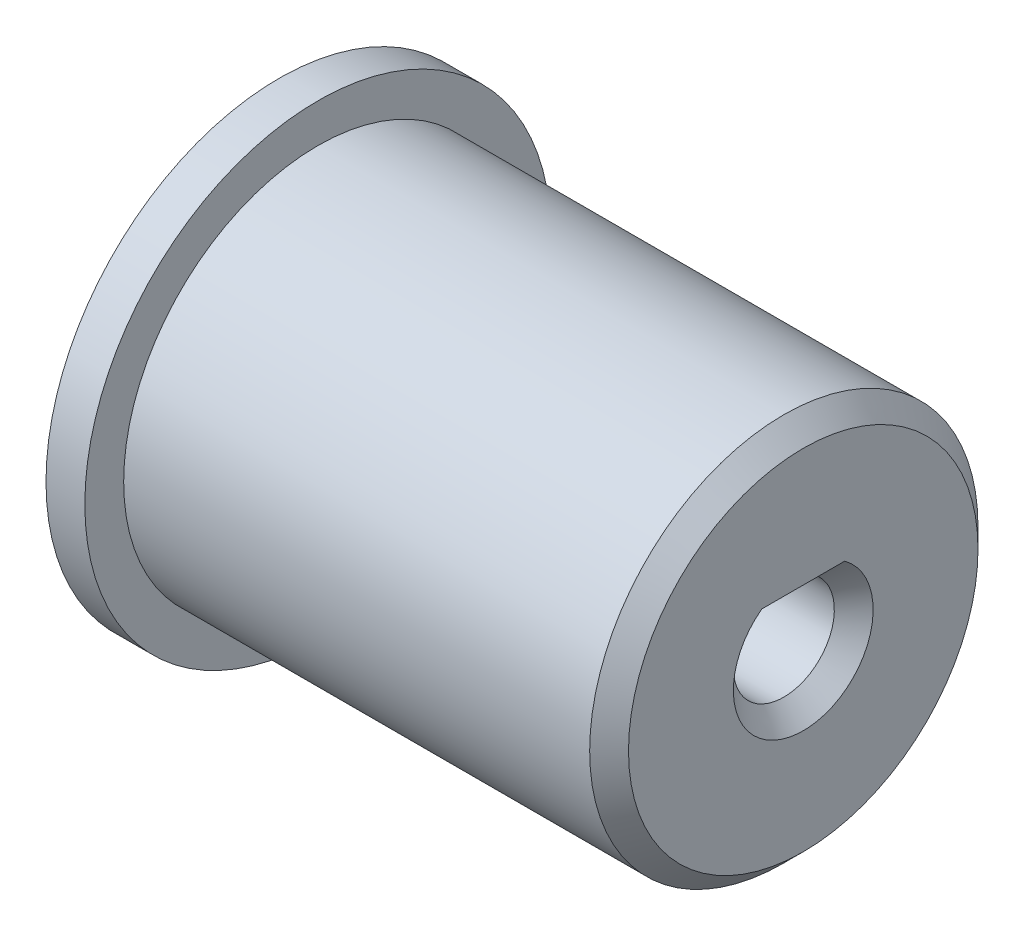
SolidWorks part; units mm, degrees
ref_plane "Ebene vorne" through (0, 0, 0) normal (0, 0, 1) x (1, 0, 0)
ref_plane "Ebene oben" through (0, 0, 0) normal (0, 1, 0) x (1, 0, 0)
ref_plane "Ebene rechts" through (0, 0, 0) normal (1, 0, 0) x (0, 0, -1)
sketch "Skizze2" plane through (0, 0, 0) normal (1, 0, 0) x (0, 0, -1)
  circle A0 centre (0, 0) radius 10
  dimension "D1" = 20
extrude "Aufsatz-Linear austragen1" add sketch "Skizze2" along normal blind 25
sketch "Skizze3" plane through (0, 0, 0) normal (-1, 0, 0) x (0, 0, 1)
  circle A0 centre (0, 0) radius 12
  dimension "D1" = 24
extrude "Aufsatz-Linear austragen2" add sketch "Skizze3" along normal blind 2
sketch "Skizze4" plane through (25, 0, 0) normal (1, 0, 0) x (0, 0, -1)
  line L0 (-1.7748, 1.9) -> (1.7748, 1.9)
  line L1 (-6.4521, 0) -> (8.6873, 0) construction
  arc A0 (-1.7748, 1.9) -> (1.7748, 1.9) centre (0, 0) ccw
  point P5 (0, -2.6)
  dimension "D1" = 2.6
  dimension "D2" = 4.5
extrude "Schnitt-Linear austragen1" cut sketch "Skizze4" against normal blind 15
chamfer "Fase1" distance 1 angle 45 2 edges at (25, 1.9, 0) (25, -2.6, 0)
chamfer "Fase2" distance 1 angle 45 1 edges at (25, 0, -10)
hole_wizard "Ø3.1 (3.1) Durchmesser Bohrung1" positions "Skizze5" profile "Skizze6" hole size "Ø3.1" standard "ISO"
sketch "Skizze5" plane through (-2, 0, 0) normal (-1, 0, 0) x (0, 0, 1)
  line L0 (0, 0) -> (-50000, 0) construction
  line L1 (0, 0) -> (0, -50000) construction
  point P5 (-4.25, 0)
  point P7 (4.25, 0)
  dimension "D1" = 8.5
sketch "Skizze6" plane through (-2, 0, 4.25) normal (0, 1, 0) x (0, 0, 1)
  line L0 (0, 0) -> (0, 7.9313)
  line L1 (0, 7.9313) -> (1.55, 7)
  line L2 (1.55, 7) -> (1.55, 0)
  line L5 (1.55, 0) -> (0, 0)
  line L10 (0, 7.9313) -> (-1.55, 7) construction
  line L11 (0, -6.35) -> (0, 107.95) construction
  dimension "Bohrerdurchmesser" = 3.1
  dimension "Bohrungstiefe" = 7
  dimension "Spitzenwinkel" = 118
chamfer "Fase3" distance 1 angle 45 2 edges at (-2, 0, 5.8) (-2, 0, -2.7)
